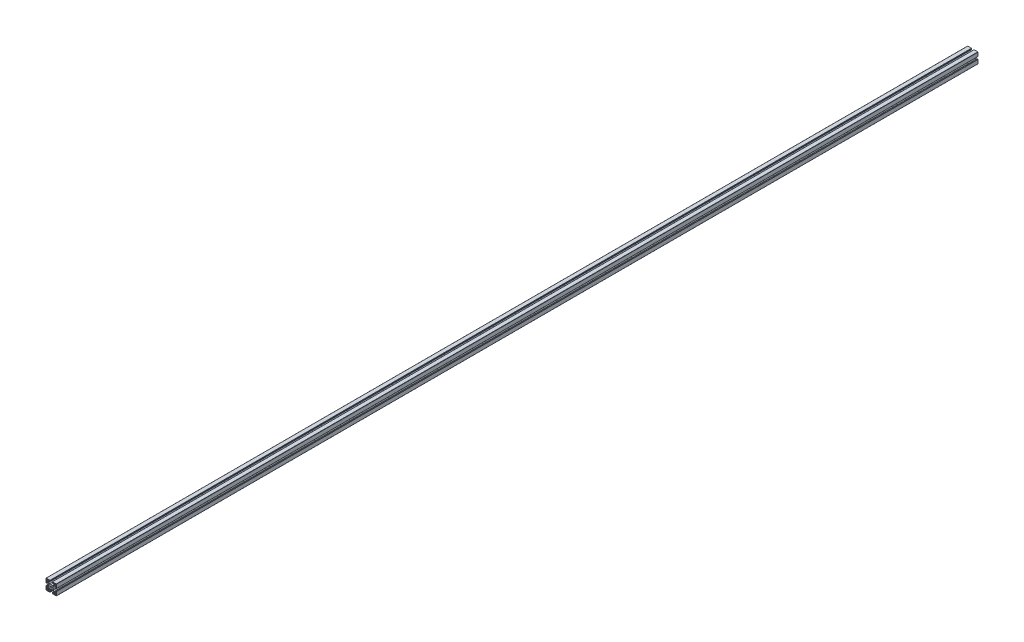
SolidWorks part; units mm, degrees
ref_plane "Front Plane" through (0, 0, 0) normal (0, 0, 1) x (1, 0, 0)
ref_plane "Top Plane" through (0, 0, 0) normal (0, 1, 0) x (1, 0, 0)
ref_plane "Right Plane" through (0, 0, 0) normal (1, 0, 0) x (0, 0, -1)
sketch "Sketch1" plane through (0, 0, 0) normal (0, 0, 1) x (1, 0, 0)
  line L0 (-19.8, 4.2) -> (-15.3, 4.2)
  line L1 (19.8, -19.8) -> (-19.8, -19.8)
  line L2 (19.8, -19.8) -> (19.8, 19.8)
  line L3 (19.8, 19.8) -> (-19.8, 19.8)
  line L4 (-19.8, -19.8) -> (-19.8, 19.8)
  line L5 (19.8, -19.8) -> (-19.8, 19.8) construction
  line L6 (19.8, 19.8) -> (-19.8, -19.8) construction
  line L7 (-15.3, 4.2) -> (-15.3, 6.9)
  line L8 (-15.3, 6.9) -> (-17.1, 6.9)
  line L9 (-17.1, 6.9) -> (-17.1, 10.1)
  line L10 (-17.1, 10.1) -> (-12.0092, 10.1)
  line L11 (-12.0092, 10.1) -> (-5.27, 3.3608)
  line L12 (-5.27, 3.3608) -> (-5.27, 0)
  line L13 (-4.2, 19.8) -> (-4.2, 15.3)
  line L14 (-4.2, 15.3) -> (-6.9, 15.3)
  line L15 (-6.9, 15.3) -> (-6.9, 17.1)
  line L16 (-6.9, 17.1) -> (-10.1, 17.1)
  line L17 (-10.1, 17.1) -> (-10.1, 12.0092)
  line L18 (-10.1, 12.0092) -> (-3.3608, 5.27)
  line L19 (-3.3608, 5.27) -> (0, 5.27)
  line L20 (5.27, 3.3608) -> (5.27, 0)
  line L21 (12.0092, 10.1) -> (5.27, 3.3608)
  line L22 (17.1, 10.1) -> (12.0092, 10.1)
  line L23 (17.1, 6.9) -> (17.1, 10.1)
  line L24 (15.3, 6.9) -> (17.1, 6.9)
  line L25 (15.3, 4.2) -> (15.3, 6.9)
  line L26 (19.8, 4.2) -> (15.3, 4.2)
  line L27 (4.2, 19.8) -> (4.2, 15.3)
  line L28 (4.2, 15.3) -> (6.9, 15.3)
  line L29 (6.9, 15.3) -> (6.9, 17.1)
  line L30 (6.9, 17.1) -> (10.1, 17.1)
  line L31 (10.1, 17.1) -> (10.1, 12.0092)
  line L32 (-19.8, -19.8) -> (19.8, -19.8)
  line L33 (-19.8, -19.8) -> (-19.8, 19.8)
  line L34 (-19.8, 19.8) -> (19.8, 19.8)
  line L35 (19.8, -19.8) -> (19.8, 19.8)
  line L36 (10.1, 12.0092) -> (3.3608, 5.27)
  line L37 (3.3608, 5.27) -> (0, 5.27)
  line L38 (3.3608, -5.27) -> (0, -5.27)
  line L39 (10.1, -12.0092) -> (3.3608, -5.27)
  line L40 (10.1, -17.1) -> (10.1, -12.0092)
  line L41 (6.9, -17.1) -> (10.1, -17.1)
  line L42 (6.9, -15.3) -> (6.9, -17.1)
  line L43 (4.2, -15.3) -> (6.9, -15.3)
  line L44 (4.2, -19.8) -> (4.2, -15.3)
  line L45 (19.8, -4.2) -> (15.3, -4.2)
  line L46 (15.3, -4.2) -> (15.3, -6.9)
  line L47 (15.3, -6.9) -> (17.1, -6.9)
  line L48 (17.1, -6.9) -> (17.1, -10.1)
  line L49 (17.1, -10.1) -> (12.0092, -10.1)
  line L50 (-19.8, 19.8) -> (-19.8, -19.8)
  line L51 (-19.8, 19.8) -> (19.8, 19.8)
  line L52 (19.8, 19.8) -> (19.8, -19.8)
  line L53 (-19.8, -19.8) -> (19.8, -19.8)
  line L54 (12.0092, -10.1) -> (5.27, -3.3608)
  line L55 (5.27, -3.3608) -> (5.27, 0)
  line L56 (-5.27, -3.3608) -> (-5.27, 0)
  line L57 (-12.0092, -10.1) -> (-5.27, -3.3608)
  line L58 (-17.1, -10.1) -> (-12.0092, -10.1)
  line L59 (-17.1, -6.9) -> (-17.1, -10.1)
  line L60 (-15.3, -6.9) -> (-17.1, -6.9)
  line L61 (-15.3, -4.2) -> (-15.3, -6.9)
  line L62 (-19.8, -4.2) -> (-15.3, -4.2)
  line L63 (-4.2, -19.8) -> (-4.2, -15.3)
  line L64 (-4.2, -15.3) -> (-6.9, -15.3)
  line L65 (-6.9, -15.3) -> (-6.9, -17.1)
  line L66 (-6.9, -17.1) -> (-10.1, -17.1)
  line L67 (-10.1, -17.1) -> (-10.1, -12.0092)
  line L68 (19.8, 19.8) -> (-19.8, 19.8)
  line L69 (19.8, 19.8) -> (19.8, -19.8)
  line L70 (19.8, -19.8) -> (-19.8, -19.8)
  line L71 (-19.8, 19.8) -> (-19.8, -19.8)
  line L72 (-10.1, -12.0092) -> (-3.3608, -5.27)
  line L73 (-3.3608, -5.27) -> (0, -5.27)
  line L74 (18.3, 11.7) -> (11.7, 11.7)
  line L75 (7.7, -7.7) -> (-7.7, -7.7)
  line L76 (7.7, -7.7) -> (7.7, 7.7)
  line L77 (7.7, 7.7) -> (-7.7, 7.7)
  line L78 (-7.7, -7.7) -> (-7.7, 7.7)
  line L79 (7.7, -7.7) -> (-7.7, 7.7) construction
  line L80 (7.7, 7.7) -> (-7.7, -7.7) construction
  line L81 (-18.3, 18.3) -> (-11.7, 18.3)
  line L82 (-18.3, 18.3) -> (-18.3, 11.7)
  line L83 (-18.3, 11.7) -> (-11.7, 11.7)
  line L84 (-11.7, 18.3) -> (-11.7, 11.7)
  line L85 (18.3, 18.3) -> (18.3, 11.7)
  line L86 (18.3, 18.3) -> (11.7, 18.3)
  line L87 (11.7, 18.3) -> (11.7, 11.7)
  line L88 (11.7, -18.3) -> (11.7, -11.7)
  line L89 (18.3, -18.3) -> (11.7, -18.3)
  line L90 (18.3, -18.3) -> (18.3, -11.7)
  line L91 (18.3, -11.7) -> (11.7, -11.7)
  line L92 (-18.3, -11.7) -> (-11.7, -11.7)
  line L93 (-18.3, -18.3) -> (-18.3, -11.7)
  line L94 (-18.3, -18.3) -> (-11.7, -18.3)
  line L95 (-11.7, -18.3) -> (-11.7, -11.7)
  circle A0 centre (0, 0) radius 3.45
  point P0 (0, 0)
  point P7 (0, 0)
  point P85 (0, 0)
  point P103 (0, 0)
  dimension "D17" = 6.9
  dimension "D1" = 39.6
  dimension "D2" = 39.6
  dimension "D3" = 4.5
  dimension "D4" = 15.6
  dimension "D5" = 2.7
  dimension "D6" = 2.7
  dimension "D7" = 1.35
  dimension "D8" = 9.7
  dimension "D9" = 5.27
  dimension "D11" = 15.4
  dimension "D12" = 15.4
  dimension "D13" = 1.5
  dimension "D14" = 6.6
  dimension "D15" = 6.6
  dimension "D10" = 4
  dimension "D16" = 4
extrude "Boss-Extrude3" add sketch "Sketch1" along normal blind 3500 contours L77 L76 L21 L22 L23 L24 L25 L26 L2 L3 L27 L28 L29 L30 L31 L36 L87 L86 L85 L74 | L76 L75 L39 L40 L41 L42 L43 L44 L1 L2 L45 L46 L47 L48 L49 L54 L91 L90 L89 L88 | L75 L78 L57 L58 L59 L60 L61 L62 L4 L53 L63 L64 L65 L66 L67 L72 L95 L94 L93 L92 | L11 L78 L77 L18 L17 L16 L15 L14 L13 L3 L4 L0 L7 L8 L9 L10 L81 L84 L83 L82 | L54 L76 L21 L20 L55 | L78 L75 L72 L73 L38 L39 L76 L54 L55 L20 L21 L77 L36 L37 L19 L18 L11 L12 L56 L57 A0 | L36 L77 L18 L19 L37 | L78 L57 L56 L12 L11 | L75 L39 L38 L73 L72
fillet "Fillet1" radius 0.8 72 edges at (-11.7, -11.7, 1750) (-18.3, -11.7, 1750) (-18.3, -18.3, 1750) (-11.7, -18.3, 1750) (11.7, -11.7, 1750) (11.7, -18.3, 1750) (18.3, -18.3, 1750) (18.3, -11.7, 1750) (-18.3, 18.3, 1750) (-18.3, 11.7, 1750) (-11.7, 11.7, 1750) (-11.7, 18.3, 1750) (11.7, 11.7, 1750) (18.3, 11.7, 1750) (18.3, 18.3, 1750) (11.7, 18.3, 1750) (-7.7, 5.7908, 1750) (-12.0092, 10.1, 1750) (-17.1, 10.1, 1750) (-17.1, 6.9, 1750) (-15.3, 6.9, 1750) (-15.3, 4.2, 1750) (-19.8, 4.2, 1750) (-19.8, 19.8, 1750) (-4.2, 19.8, 1750) (-4.2, 15.3, 1750) (-6.9, 15.3, 1750) (-6.9, 17.1, 1750) (-10.1, 17.1, 1750) (-10.1, 12.0092, 1750) (5.7908, 7.7, 1750) (10.1, 12.0092, 1750) (10.1, 17.1, 1750) (6.9, 17.1, 1750) (4.2, 15.3, 1750) (4.2, 19.8, 1750) (19.8, 19.8, 1750) (19.8, 4.2, 1750) (15.3, 4.2, 1750) (15.3, 6.9, 1750) (17.1, 6.9, 1750) (17.1, 10.1, 1750) (12.0092, 10.1, 1750) (7.7, 5.7908, 1750) (7.7, -5.7908, 1750) (12.0092, -10.1, 1750) (17.1, -10.1, 1750) (17.1, -6.9, 1750) (15.3, -6.9, 1750) (15.3, -4.2, 1750) (19.8, -4.2, 1750) (19.8, -19.8, 1750) (4.2, -19.8, 1750) (4.2, -15.3, 1750) (6.9, -17.1, 1750) (10.1, -17.1, 1750) (10.1, -12.0092, 1750) (5.7908, -7.7, 1750) (-5.7908, -7.7, 1750) (-10.1, -12.0092, 1750) (-10.1, -17.1, 1750) (-6.9, -17.1, 1750) (-6.9, -15.3, 1750) (-4.2, -15.3, 1750) (-4.2, -19.8, 1750) (-19.8, -19.8, 1750) (-19.8, -4.2, 1750) (-15.3, -4.2, 1750) (-15.3, -6.9, 1750) (-17.1, -10.1, 1750) (-12.0092, -10.1, 1750) (-7.7, -5.7908, 1750)
